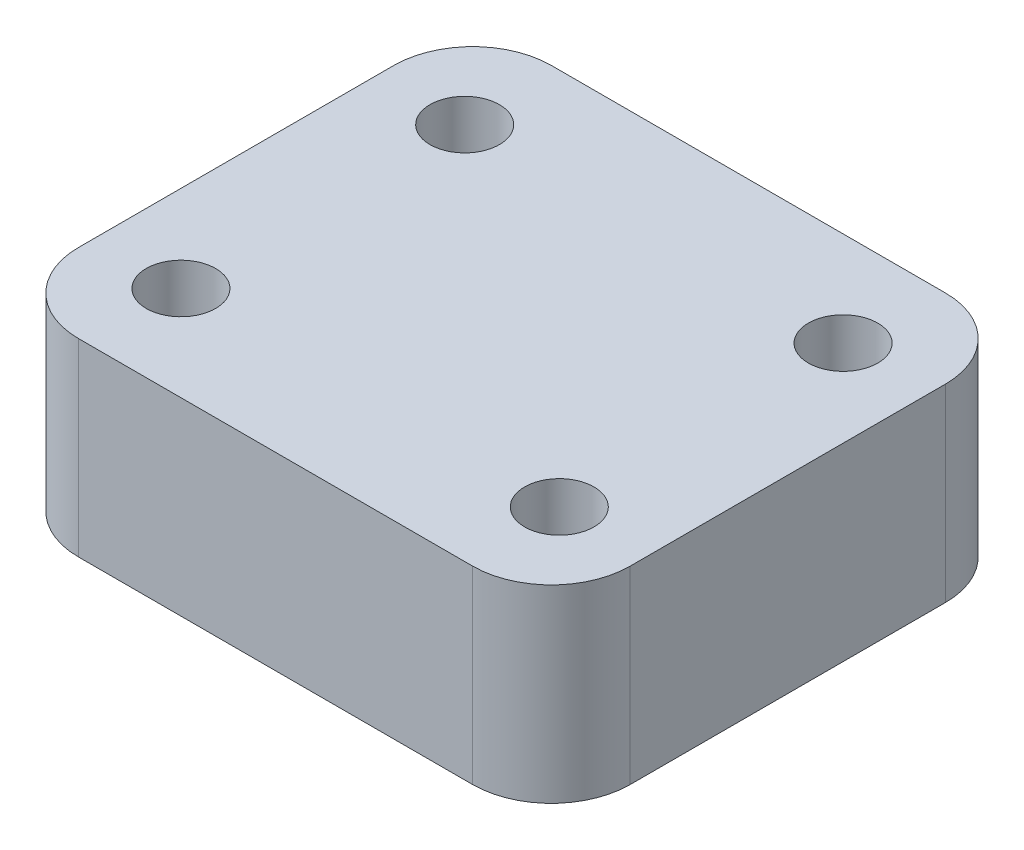
SolidWorks part; units mm, degrees
ref_plane "Front Plane" through (0, 0, 0) normal (0, 0, 1) x (1, 0, 0)
ref_plane "Top Plane" through (0, 0, 0) normal (0, 1, 0) x (1, 0, 0)
ref_plane "Right Plane" through (0, 0, 0) normal (1, 0, 0) x (0, 0, -1)
sketch "Sketch1" plane through (0, 0, 0) normal (0, 1, 0) x (1, 0, 0)
  line L1 (-17.5, 15) -> (17.5, 15)
  line L2 (-17.5, 15) -> (-17.5, -15)
  line L3 (-17.5, -15) -> (17.5, -15)
  line L4 (17.5, 15) -> (17.5, -15)
  line L5 (-17.5, 15) -> (17.5, -15) construction
  line L6 (-17.5, -15) -> (17.5, 15) construction
  point P0 (0, 0)
  dimension "D1" = 35
  dimension "D2" = 30
extrude "Boss-Extrude1" add sketch "Sketch1" along normal blind 12
sketch "Sketch2" plane through (0, 12, 0) normal (0, 1, 0) x (1, 0, 0)
  line L1 (-12, 9) -> (12, 9) construction
  line L2 (-12, 9) -> (-12, -9) construction
  line L3 (-12, -9) -> (12, -9) construction
  line L4 (12, 9) -> (12, -9) construction
  line L5 (-12, 9) -> (12, -9) construction
  line L6 (-12, -9) -> (12, 9) construction
  circle A0 centre (-12, 9) radius 2.2
  circle A1 centre (12, 9) radius 2.2
  circle A2 centre (12, -9) radius 2.2
  circle A3 centre (-12, -9) radius 2.2
  point P0 (0, 0)
  dimension "D3" = 4.4
  dimension "D1" = 24
  dimension "D2" = 18
extrude "Cut-Extrude1" cut sketch "Sketch2" against normal through all
fillet "Fillet1" radius 5 4 edges at (-17.5, 6, -15) (17.5, 6, -15) (17.5, 6, 15) (-17.5, 6, 15)
